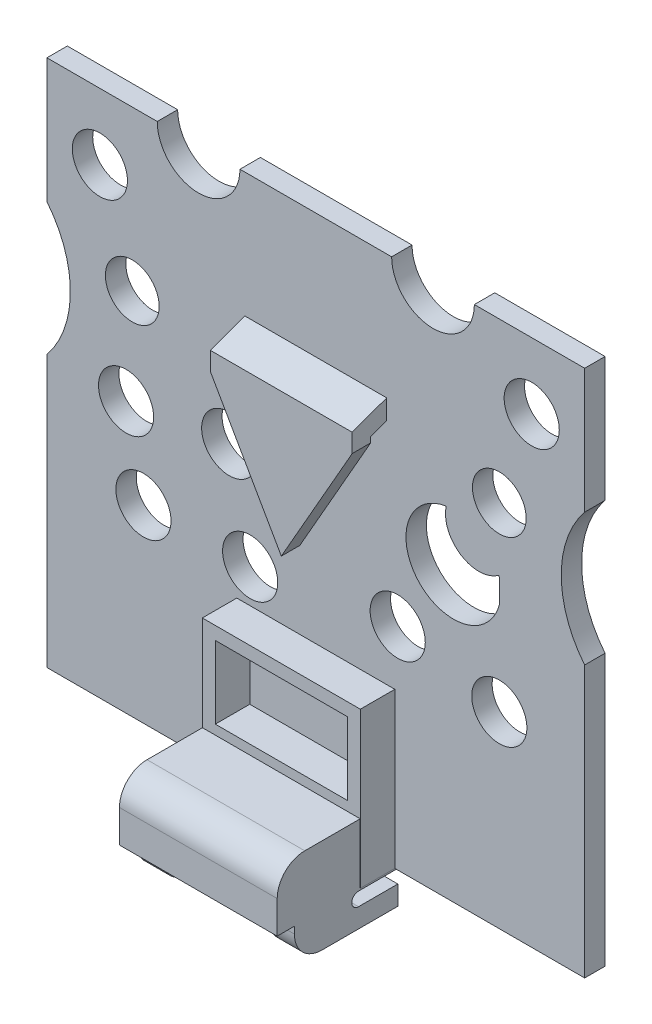
SolidWorks part; units mm, degrees
material "ABS"
ref_plane "Front Plane" through (0, 0, 0) normal (0, 0, 1) x (1, 0, 0)
ref_plane "Top Plane" through (0, 0, 0) normal (0, 1, 0) x (1, 0, 0)
ref_plane "Right Plane" through (0, 0, 0) normal (1, 0, 0) x (0, 0, -1)
sketch "Sketch1" plane through (0, 0, 0) normal (0, 0, 1) x (1, 0, 0)
  line L0 (0, 24.3205) -> (0, -24.3205) construction
  line L1 (-24.765, -24.3205) -> (24.765, -24.3205)
  line L2 (-24.765, -24.3205) -> (-24.765, 24.3205)
  line L3 (-24.765, 24.3205) -> (-14.605, 24.3205)
  line L4 (24.765, -24.3205) -> (24.765, 24.3205)
  line L5 (-24.765, -24.3205) -> (24.765, 24.3205) construction
  line L6 (-24.765, 24.3205) -> (24.765, -24.3205) construction
  line L7 (14.605, 24.3205) -> (24.765, 24.3205)
  line L8 (-6.985, 24.3205) -> (6.985, 24.3205)
  arc A0 (6.985, 24.3205) -> (14.605, 24.3205) centre (10.795, 24.3205) ccw
  circle A1 centre (19.8882, 18.2245) radius 2.54
  circle A2 centre (16.9037, 9.652) radius 2.4765
  circle A3 centre (-16.9037, 9.652) radius 2.4765
  circle A4 centre (-19.8882, 18.2245) radius 2.54
  arc A5 (-6.985, 24.3205) -> (-14.605, 24.3205) centre (-10.795, 24.3205) cw
  point P0 (0, 0)
  dimension "D3" = 7.62
  dimension "D5" = 5.08
  dimension "D6" = 2.3368
  dimension "D7" = 3.556
  dimension "D8" = 4.953
  dimension "D10" = 5.3848
  dimension "D1" = 49.53
  dimension "D2" = 48.641
  dimension "D4" = 10.16
  dimension "D9" = 12.192
extrude "Boss-Extrude1" add sketch "Sketch1" along normal blind 1.8796
sketch "Sketch2" plane through (0, 0, 1.8796) normal (0, 0, 1) x (1, 0, 0)
  line L0 (-24.765, -24.3205) -> (24.765, -24.3205) construction
  line L1 (16.9037, 9.652) -> (16.9037, -7.0231) construction
  line L4 (24.765, -24.3205) -> (24.765, 24.3205) construction
  line L6 (-24.765, 24.3205) -> (-24.765, -24.3205) construction
  line L7 (-14.605, 24.3205) -> (-24.765, 24.3205) construction
  circle A0 centre (-7.9756, 1.9177) radius 2.54
  circle A1 centre (-17.4752, 0.5715) radius 2.54
  circle A2 centre (-6.0452, -6.9215) radius 2.54
  circle A3 centre (-15.875, -6.9215) radius 2.54
  circle A4 centre (7.5438, -4.8895) radius 2.54
  circle A5 centre (16.9037, -7.0231) radius 2.54
  arc A10 (12.011, 6.947) -> (16.8665, 3.8595) centre (12.6746, 2.6289) ccw
  arc A11 (12.011, 6.947) -> (16.9037, 3.8879) centre (15.0189, 6.3155) ccw
  dimension "D1" = 5.08
  dimension "D2" = 14.7574
  dimension "D3" = 14.6812
  dimension "D4" = 16.891
  dimension "D5" = 6.35
  dimension "D6" = 14.859
  dimension "D7" = 16.1798
  dimension "D8" = 4.7498
  dimension "D9" = 14.2494
  dimension "D12" = 8.7376
  dimension "D13" = 7.7216
  dimension "D14" = 22.5806
  dimension "D15" = 6.1468
  dimension "D10" = 21.209
  dimension "D11" = 19.8628
extrude "Cut-Extrude1" cut sketch "Sketch2" against normal through all
sketch "Sketch3" plane through (0, 0, 1.8796) normal (0, 0, 1) x (1, 0, 0)
  line L0 (24.765, -24.3205) -> (24.765, 24.3205) construction
  line L1 (24.765, 24.3205) -> (14.605, 24.3205) construction
  line L2 (22.606, 6.7437) -> (24.765, 6.7437) construction
  line L3 (24.765, 12.8397) -> (24.765, 0.6477)
  arc A0 (24.765, 12.8397) -> (24.765, 0.6477) centre (32.2916, 6.7437) ccw
  dimension "D1" = 11.4808
  dimension "D2" = 12.192
  dimension "D3" = 2.159
extrude "Cut-Extrude2" cut sketch "Sketch3" against normal through all
mirror "Mirror1" about plane through (0, 0, 0) normal (1, 0, 0) of "Cut-Extrude2"
sketch "Sketch4" plane through (0, 0, 0) normal (1, 0, 0) x (0, 0, -1)
  line L0 (-1.8796, 12.8397) -> (-5.0546, 11.6841)
  line L1 (-5.0546, 11.6841) -> (-5.0546, -1.4605)
  line L2 (-5.0546, -1.4605) -> (-3.3528, -1.4605)
  line L3 (-3.3528, -1.4605) -> (-3.3528, 10.4925)
  line L4 (-3.3528, 10.4925) -> (-1.8796, 11.0287)
  line L5 (-1.8796, 12.8397) -> (-1.8796, 0.6477) construction
  line L6 (-1.8796, 11.0287) -> (-1.8796, 12.8397)
  line L7 (-1.8796, 12.8397) -> (-1.8796, 24.3205) construction
  dimension "D1" = 1.7018
  dimension "D2" = 14.3002
  dimension "D3" = 3.175
  dimension "D4" = 1.7018
  dimension "D5" = 110
extrude "Boss-Extrude2" add sketch "Sketch4" along normal mid plane 13.0556
sketch "Sketch5" plane through (0, 0, 5.0546) normal (0, 0, 1) x (1, 0, 0)
  line L0 (0, -1.4605) -> (6.5278, 9.9823)
  line L1 (6.5278, -1.4605) -> (-6.5278, -1.4605) construction
  line L2 (6.5278, 11.6841) -> (6.5278, -1.4605) construction
  line L3 (0, -1.4605) -> (-6.5278, 9.9823)
  line L4 (-6.5278, 11.6841) -> (-6.5278, -1.4605) construction
  line L5 (6.5278, 11.6841) -> (-6.5278, 11.6841) construction
  line L6 (-6.5278, 9.9823) -> (-6.5278, -1.4605)
  line L7 (-6.5278, -1.4605) -> (0, -1.4605)
  line L8 (6.5278, -1.4605) -> (6.5278, 9.9823)
  line M4 (-6.5278, 11.6841) -> (-6.5278, -1.4605)
  line M5 (-6.5278, -1.4605) -> (6.5278, -1.4605)
  line M6 (6.5278, -1.4605) -> (6.5278, 11.6841)
  dimension "D1" = 1.7018
extrude "Cut-Extrude4" cut sketch "Sketch5" against normal up to next contours L3 M5 M4 | L0 M5 M6
sketch "Sketch6" plane through (0, 0, 1.8796) normal (0, 0, 1) x (1, 0, 0)
  line L0 (-24.765, -24.3205) -> (24.765, -24.3205) construction
  line L1 (-7.2771, -24.3205) -> (7.2771, -24.3205)
  line L2 (-7.2771, -24.3205) -> (-7.2771, -10.033)
  line L3 (-7.2771, -10.033) -> (7.2771, -10.033)
  line L4 (7.2771, -24.3205) -> (7.2771, -10.033)
  line L5 (-7.2771, -24.3205) -> (7.2771, -10.033) construction
  line L6 (-7.2771, -10.033) -> (7.2771, -24.3205) construction
  line L7 (-6.0833, -11.2268) -> (-6.0833, -17.907)
  line L8 (-6.0833, -17.907) -> (6.0833, -17.907)
  line L9 (6.0833, -17.907) -> (6.0833, -11.2268)
  line L10 (6.0833, -11.2268) -> (-6.0833, -11.2268)
  point P0 (0, -17.1768)
  dimension "D1" = 14.5542
  dimension "D2" = 14.2875
  dimension "D3" = 6.6802
  dimension "D4" = 1.1938
  dimension "D5" = 1.1938
  dimension "D6" = 1.1938
extrude "Boss-Extrude3" add sketch "Sketch6" along normal blind 3.175
sketch "Sketch7" plane through (0, 0, 0) normal (1, 0, 0) x (0, 0, -1)
  line L0 (-5.0546, -18.7833) -> (-12.7, -18.7833)
  line L1 (-5.0546, -24.3205) -> (-5.0546, -10.033) construction
  line L2 (-12.7, -18.7833) -> (-12.7, -24.3205)
  line L3 (-12.7, -24.3205) -> (-11.1125, -24.3205)
  line L4 (-11.1125, -24.3205) -> (-11.1125, -27.4955)
  line L5 (-11.1125, -27.4955) -> (-1.5875, -27.4955)
  line L6 (-1.5875, -27.4955) -> (-1.5875, -24.3205)
  line L7 (-1.5875, -24.3205) -> (-5.0546, -24.3205)
  line L8 (-5.0546, -24.3205) -> (-5.0546, -18.7833)
  line L9 (0, -24.3205) -> (0, 0.6477) construction
  dimension "D1" = 12.7
  dimension "D2" = 5.5372
  dimension "D3" = 1.5875
  dimension "D4" = 3.175
  dimension "D5" = 1.5875
extrude "Boss-Extrude4" add sketch "Sketch7" along normal mid plane 14.5288
fillet "Fillet1" radius 2.54 2 edges at (0, -27.4955, 11.1125) (0, -18.7833, 12.7)
sketch "Sketch8" plane through (0, -27.4955, 0) normal (0, -1, 0) x (1, 0, 0)
  line L0 (7.2644, 12.7) -> (-7.2644, 12.7) construction
  line L1 (-4.9403, 0) -> (4.9403, 0)
  line L2 (-4.9403, 0) -> (-4.9403, 10.795)
  line L3 (-4.9403, 10.795) -> (4.9403, 10.795)
  line L4 (4.9403, 0) -> (4.9403, 10.795)
  line L5 (-4.9403, 0) -> (4.9403, 10.795) construction
  line L6 (-4.9403, 10.795) -> (4.9403, 0) construction
  line L7 (-24.765, 0) -> (24.765, 0) construction
  point P0 (0, 5.3975)
  dimension "D1" = 1.905
  dimension "D2" = 9.8806
extrude "Cut-Extrude5" cut sketch "Sketch8" against normal blind 7.9375
sketch "Sketch9" plane through (-7.2644, 0, 0) normal (-1, 0, 0) x (0, 0, 1)
  line L0 (5.207, -24.4729) -> (1.5875, -24.4729)
  line L1 (1.5875, -27.4955) -> (1.5875, -24.3205) construction
  line L2 (5.207, -25.7175) -> (1.5875, -25.7175)
  line L3 (1.5875, -25.7175) -> (1.5875, -24.4729)
  line L4 (8.5725, -27.4955) -> (1.5875, -27.4955) construction
  arc A0 (5.207, -25.7175) -> (5.207, -24.4729) centre (5.207, -25.0952) ccw
  dimension "D1" = 1.2446
  dimension "D3" = 4.2418
  dimension "D2" = 1.778
extrude "Cut-Extrude6" cut sketch "Sketch9" against normal through all
